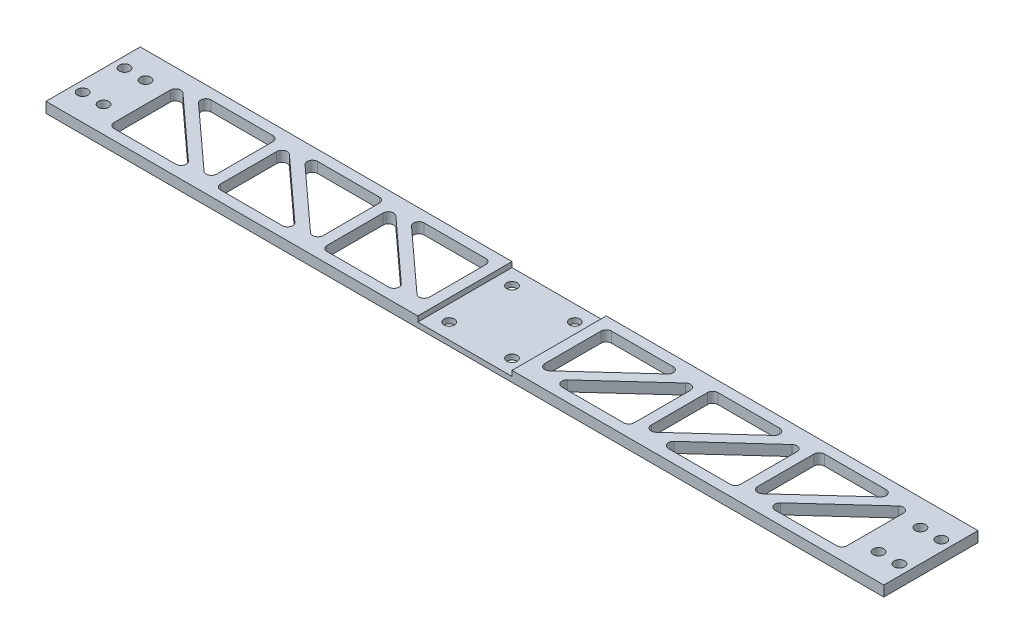
SolidWorks part; units mm, degrees
material "6061-T6 (SS)"
ref_plane "Front Plane" through (0, 0, 0) normal (0, 0, 1) x (1, 0, 0)
ref_plane "Top Plane" through (0, 0, 0) normal (0, 1, 0) x (1, 0, 0)
ref_plane "Right Plane" through (0, 0, 0) normal (1, 0, 0) x (0, 0, -1)
sketch "Sketch2" plane through (0, 0, 0) normal (1, 0, 0) x (0, 0, -1)
  line L1 (-28.575, 3.175) -> (28.575, 3.175)
  line L2 (-28.575, 3.175) -> (-28.575, -3.175)
  line L3 (-28.575, -3.175) -> (28.575, -3.175)
  line L4 (28.575, 3.175) -> (28.575, -3.175)
  line L5 (-28.575, 3.175) -> (28.575, -3.175) construction
  line L6 (-28.575, -3.175) -> (28.575, 3.175) construction
  point P0 (0, 0)
  dimension "D1" = 6.35
  dimension "D2" = 57.15
extrude "Boss-Extrude2" add sketch "Sketch2" along normal mid plane 508
hole_wizard "1/4 (0.25) Diameter Hole1" positions "Sketch4" profile "Sketch5" hole size "1/4" standard "ANSI Inch" end condition up to next
sketch "Sketch4" plane through (0, 3.175, 0) normal (0, 1, 0) x (1, 0, 0)
  line L1 (-247.65, -12.7) -> (-234.95, -12.7) construction
  line L2 (-247.65, -12.7) -> (-247.65, 12.7) construction
  line L3 (-247.65, 12.7) -> (-234.95, 12.7) construction
  line L4 (-234.95, -12.7) -> (-234.95, 12.7) construction
  line L5 (-254, 28.575) -> (-254, -28.575) construction
  line L6 (-254, 0) -> (254, 0) construction
  line L7 (254, 28.575) -> (254, -28.575) construction
  point P0 (-247.65, -12.7)
  point P2 (-247.65, 12.7)
  point P4 (-234.95, 12.7)
  point P6 (-234.95, -12.7)
  point P167 (-247.65, 0)
  dimension "D1" = 25.4
  dimension "D2" = 12.7
  dimension "D3" = 6.35
sketch "Sketch5" plane through (-247.65, 3.175, 12.7) normal (1, 0, 0) x (0, 0, 1)
  line L0 (0, 0) -> (0, 6.351)
  line L1 (0, 6.351) -> (3.175, 6.351)
  line L2 (3.175, 6.351) -> (3.175, 0)
  line L5 (3.175, 0) -> (0, 0)
  line L11 (0, -6.35) -> (0, 107.95) construction
  dimension "Thru Hole Dia." = 6.35
  dimension "Thru Hole Depth" = 6.351
mirror "Mirror1" about plane through (0, 0, 0) normal (1, 0, 0) of "1/4 (0.25) Diameter Hole1"
sketch "Sketch6" plane through (0, 3.175, 0) normal (0, 1, 0) x (1, 0, 0)
  line L0 (-222.25, 22.225) -> (-222.25, -22.225)
  line L1 (-222.25, -22.225) -> (-173.4695, -22.225)
  line L2 (-173.4695, -22.225) -> (-222.25, 22.225)
  line L3 (-212.8221, 22.225) -> (-164.0417, -22.225)
  line L4 (-164.0417, -22.225) -> (-164.0417, 22.225)
  line L5 (-164.0417, 22.225) -> (-212.8221, 22.225)
  line L6 (-197.8598, 0) -> (-193.5828, 4.6936) construction
  line L7 (-228.6, 28.575) -> (-228.6, -28.575) construction
  line L8 (254, 28.575) -> (-254, 28.575) construction
  line L9 (254, -28.575) -> (-254, -28.575) construction
  line L10 (-222.25, 0) -> (-228.6, 0) construction
  line L11 (-157.6917, 22.225) -> (-157.6917, -22.225)
  line L12 (-157.6917, -22.225) -> (-108.9112, -22.225)
  line L13 (-108.9112, -22.225) -> (-157.6917, 22.225)
  line L14 (-148.2638, 22.225) -> (-99.4833, -22.225)
  line L15 (-99.4833, -22.225) -> (-99.4833, 22.225)
  line L16 (-99.4833, 22.225) -> (-148.2638, 22.225)
  line L17 (-133.3014, 0) -> (-129.0245, 4.6936) construction
  line L18 (-93.1333, 22.225) -> (-93.1333, -22.225)
  line L19 (-93.1333, -22.225) -> (-44.3529, -22.225)
  line L20 (-44.3529, -22.225) -> (-93.1333, 22.225)
  line L21 (-83.7055, 22.225) -> (-34.925, -22.225)
  line L22 (-34.925, -22.225) -> (-34.925, 22.225)
  line L23 (-34.925, 22.225) -> (-83.7055, 22.225)
  line L24 (-68.7431, 0) -> (-64.4661, 4.6936) construction
  line L25 (-28.575, -28.575) -> (-28.575, 28.575) construction
  line L26 (-164.0417, 0) -> (-157.6917, 0) construction
  line L27 (-99.4833, 0) -> (-93.1333, 0) construction
  line L28 (28.575, 28.575) -> (28.575, -28.575) construction
  line L29 (0, -28.575) -> (0, 28.575) construction
  line L30 (-34.925, 0) -> (-28.575, 0) construction
  circle A0 centre (-234.95, 12.7) radius 3.175 construction
  dimension "D1" = 6.35
  dimension "D2" = 6.35
  dimension "D4" = 6.35
  dimension "D5" = 6.35
  dimension "D6" = 28.575
  dimension "D7" = 28.575
  dimension "D3" = 3
extrude "Cut-Extrude1" cut sketch "Sketch6" against normal up to next
fillet "Fillet1" radius 3.175 18 edges at (-93.1333, 0, 22.225) (-93.1333, 0, -22.225) (-44.3529, 0, 22.225) (-34.925, 0, 22.225) (-34.925, 0, -22.225) (-83.7055, 0, -22.225) (-148.2638, 0, -22.225) (-99.4833, 0, -22.225) (-99.4833, 0, 22.225) (-108.9112, 0, 22.225) (-157.6917, 0, 22.225) (-157.6917, 0, -22.225) (-212.8221, 0, -22.225) (-164.0417, 0, -22.225) (-164.0417, 0, 22.225) (-173.4695, 0, 22.225) (-222.25, 0, 22.225) (-222.25, 0, -22.225)
mirror "Mirror4" about plane through (0, 0, 0) normal (1, 0, 0) of "Fillet1", "Cut-Extrude1"
sketch "Sketch7" plane through (0, 3.175, 0) normal (0, 1, 0) x (1, 0, 0)
  line L0 (254, 28.575) -> (-254, 28.575) construction
  line L1 (-28.575, 28.575) -> (28.575, 28.575)
  line L2 (-28.575, 28.575) -> (-28.575, -28.575)
  line L3 (-28.575, -28.575) -> (28.575, -28.575)
  line L4 (28.575, 28.575) -> (28.575, -28.575)
  line L5 (254, -28.575) -> (-254, -28.575) construction
  line L6 (-28.575, 0) -> (28.575, 0) construction
  point P10 (0, 0)
extrude "Cut-Extrude2" cut sketch "Sketch7" against normal blind 3.175
hole_wizard "1/4 (0.25) Diameter Hole2" positions "Sketch10" profile "Sketch9" hole size "1/4" standard "ANSI Inch" end condition up to next
sketch "Sketch10" plane through (0, 0, 0) normal (0, 1, 0) x (1, 0, 0)
  line L1 (-19.05, 19.05) -> (19.05, 19.05) construction
  line L2 (-19.05, 19.05) -> (-19.05, -19.05) construction
  line L3 (-19.05, -19.05) -> (19.05, -19.05) construction
  line L4 (19.05, 19.05) -> (19.05, -19.05) construction
  line L5 (-19.05, 19.05) -> (19.05, -19.05) construction
  line L6 (-19.05, -19.05) -> (19.05, 19.05) construction
  point P2 (19.05, -19.05)
  point P87 (-19.05, 19.05)
  point P88 (-19.05, -19.05)
  point P89 (19.05, 19.05)
  dimension "D1" = 38.1
sketch "Sketch9" plane through (19.05, 0, 19.05) normal (1, 0, 0) x (0, 0, 1)
  line L0 (0, 0) -> (0, 3.175)
  line L1 (0, 3.175) -> (3.175, 3.175)
  line L2 (3.175, 3.175) -> (3.175, 0)
  line L5 (3.175, 0) -> (0, 0)
  line L11 (0, -6.35) -> (0, 107.95) construction
  dimension "Thru Hole Dia." = 6.35
  dimension "Thru Hole Depth" = 3.175
